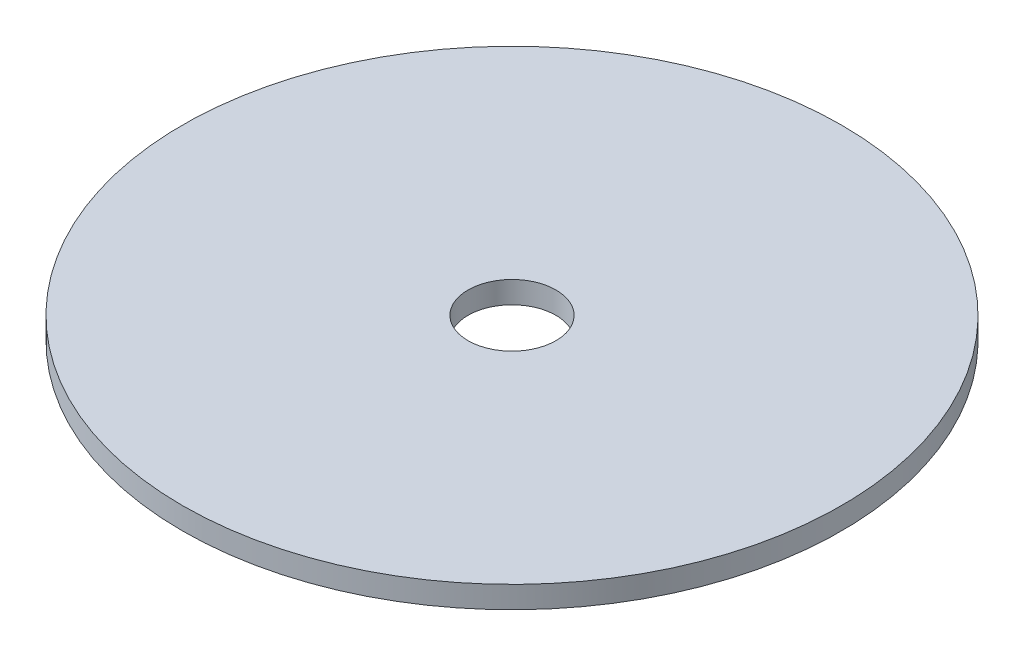
SolidWorks part; units mm, degrees
ref_plane "前基準面" through (0, 0, 0) normal (0, 0, 1) x (1, 0, 0)
ref_plane "上基準面" through (0, 0, 0) normal (0, 1, 0) x (1, 0, 0)
ref_plane "右基準面" through (0, 0, 0) normal (1, 0, 0) x (0, 0, -1)
sketch "草圖1" plane through (0, 0, 0) normal (0, 1, 0) x (1, 0, 0)
  circle A0 centre (0, 0) radius 75
  circle A1 centre (0, 0) radius 10
  dimension "D1" = 150
  dimension "D2" = 20
extrude "填料-伸長1" add sketch "草圖1" along normal blind 5
